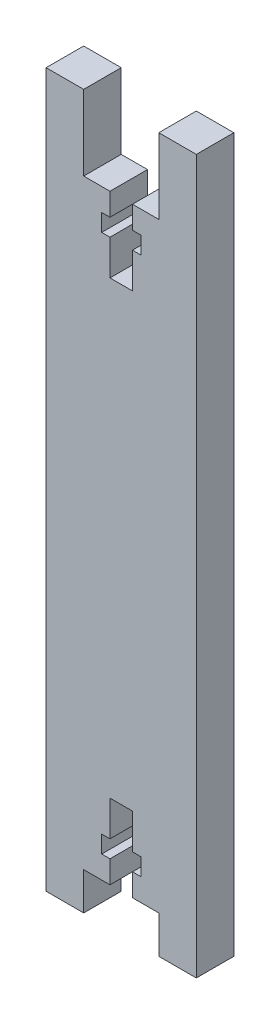
SolidWorks part; units mm, degrees
ref_plane "Front Plane" through (0, 0, 0) normal (0, 0, 1) x (1, 0, 0)
ref_plane "Top Plane" through (0, 0, 0) normal (0, 1, 0) x (1, 0, 0)
ref_plane "Right Plane" through (0, 0, 0) normal (1, 0, 0) x (0, 0, -1)
sketch "Sketch1" plane through (0, 0, 0) normal (0, 0, 1) x (1, 0, 0)
  line L0 (-1.5, 0) -> (-5, 0)
  line L1 (-5, -5) -> (-10, -5)
  line L2 (-10, -5) -> (-10, 0)
  line L3 (-5, -5) -> (-5, 0)
  line L4 (1.5, 0) -> (5, 0)
  line L5 (5, 0) -> (5, -5)
  line L6 (5, -5) -> (10, -5)
  line L7 (10, -5) -> (10, 0)
  line L8 (-1.5, 0) -> (1.5, 0) construction
  line L9 (1.5, 0) -> (1.5, 3)
  line L10 (1.5, 5.3) -> (2.6, 5.3)
  line L11 (-2.6, 3) -> (-2.6, 5.3)
  line L12 (2.6, 3) -> (1.5, 3)
  line L13 (1.5, 5.3) -> (1.5, 10)
  line L14 (1.5, 10) -> (-1.5, 10)
  line L15 (-1.5, 10) -> (-1.5, 5.3)
  line L16 (-1.5, 3) -> (-2.6, 3)
  line L17 (2.6, 5.3) -> (2.6, 3)
  line L18 (-2.6, 5.3) -> (-1.5, 5.3)
  line L19 (-1.5, 3) -> (-1.5, 0)
  line L20 (0, 10) -> (0, 0) construction
  line L21 (-10, 0) -> (-10, 80)
  line L23 (10, 80) -> (10, 0)
  line L24 (0, 70) -> (0, 80) construction
  line L25 (-1.5, 80) -> (1.5, 80) construction
  line L26 (-1.5, 77) -> (-1.5, 80)
  line L27 (-2.6, 74.7) -> (-1.5, 74.7)
  line L28 (2.6, 74.7) -> (2.6, 77)
  line L29 (-1.5, 77) -> (-2.6, 77)
  line L30 (-1.5, 70) -> (-1.5, 74.7)
  line L31 (1.5, 70) -> (-1.5, 70)
  line L32 (1.5, 74.7) -> (1.5, 70)
  line L33 (2.6, 77) -> (1.5, 77)
  line L34 (-2.6, 77) -> (-2.6, 74.7)
  line L35 (1.5, 74.7) -> (2.6, 74.7)
  line L36 (1.5, 80) -> (1.5, 77)
  line L37 (10, 85) -> (10, 80)
  line L39 (5, 80) -> (5, 85)
  line L40 (1.5, 80) -> (5, 80)
  line L41 (-5, 85) -> (-5, 80)
  line L42 (-10, 85) -> (-10, 80)
  line L44 (-1.5, 80) -> (-5, 80)
  line L45 (-10, 40) -> (10, 40) construction
  line L46 (-10, 85) -> (-10, 90)
  line L55 (-10, 90) -> (-5, 90)
  line L56 (-5, 90) -> (-5, 85)
  line L57 (5, 85) -> (5, 90)
  line L58 (5, 90) -> (10, 90)
  line L59 (10, 90) -> (10, 85)
  dimension "D1" = 5
  dimension "D2" = 5
  dimension "D3" = 5.2
  dimension "D4" = 3
  dimension "D5" = 2.3
  dimension "D6" = 3
  dimension "D7" = 10
  dimension "D8" = 45
  dimension "D9" = 5
  dimension "D14" = 10
extrude "Boss-Extrude1" add sketch "Sketch1" along normal blind 5
